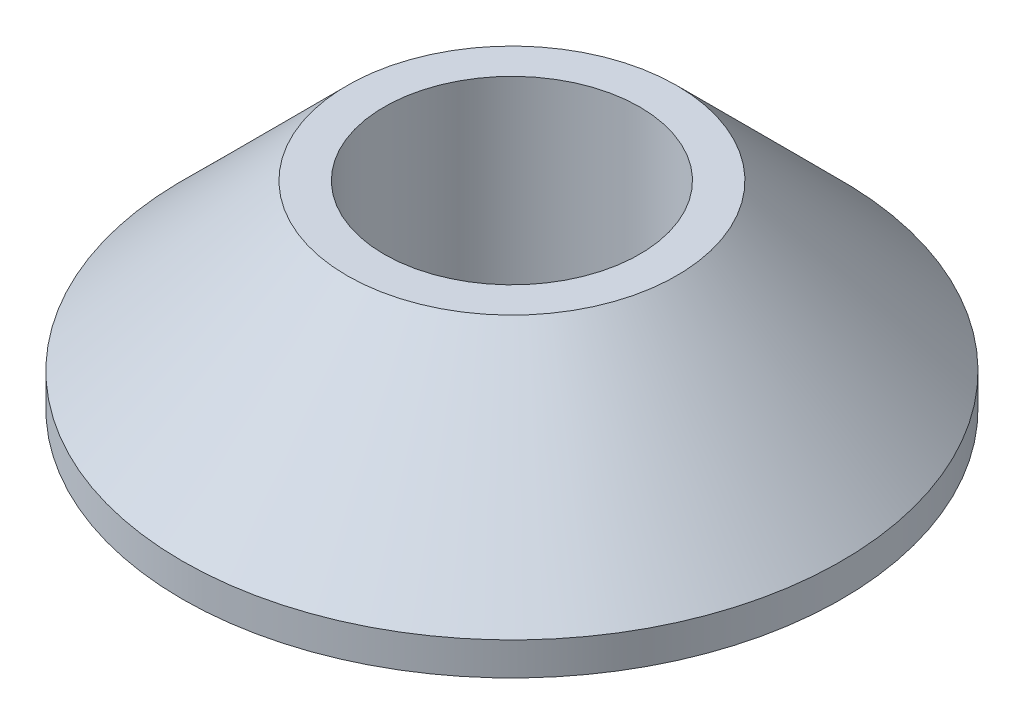
SolidWorks part; units mm, degrees
material "3D printed plastic"
ref_plane "Front Plane" through (0, 0, 0) normal (0, 0, 1) x (1, 0, 0)
ref_plane "Top Plane" through (0, 0, 0) normal (0, 1, 0) x (1, 0, 0)
ref_plane "Right Plane" through (0, 0, 0) normal (1, 0, 0) x (0, 0, -1)
sketch "Sketch1" plane through (0, 0, 0) normal (0, 1, 0) x (1, 0, 0)
  circle A0 centre (0, 0) radius 15.5
  circle A1 centre (0, 0) radius 40
  dimension "D1" = 31
  dimension "D2" = 80
extrude "Boss-Extrude1" add sketch "Sketch1" along normal blind 24
chamfer "Chamfer1" distance 20 angle 45 1 edges at (0, 24, 40)
sketch "Sketch2" plane through (0, 0, 0) normal (0, -1, 0) x (1, 0, 0)
  line L0 (0, 26) -> (0, 0) construction
  line L1 (26, 0) -> (0, 0) construction
  line L2 (0, -26) -> (0, 0) construction
  line L3 (-26, 0) -> (0, 0) construction
  circle A0 centre (0, 26) radius 1.5
  circle A1 centre (26, 0) radius 1.5
  circle A2 centre (0, -26) radius 1.5
  circle A3 centre (-26, 0) radius 1.5
  point P13 (0, 0)
  dimension "D1" = 26
  dimension "D2" = 3
  dimension "D3" = 4
extrude "Cut-Extrude1" cut sketch "Sketch2" against normal blind 10
